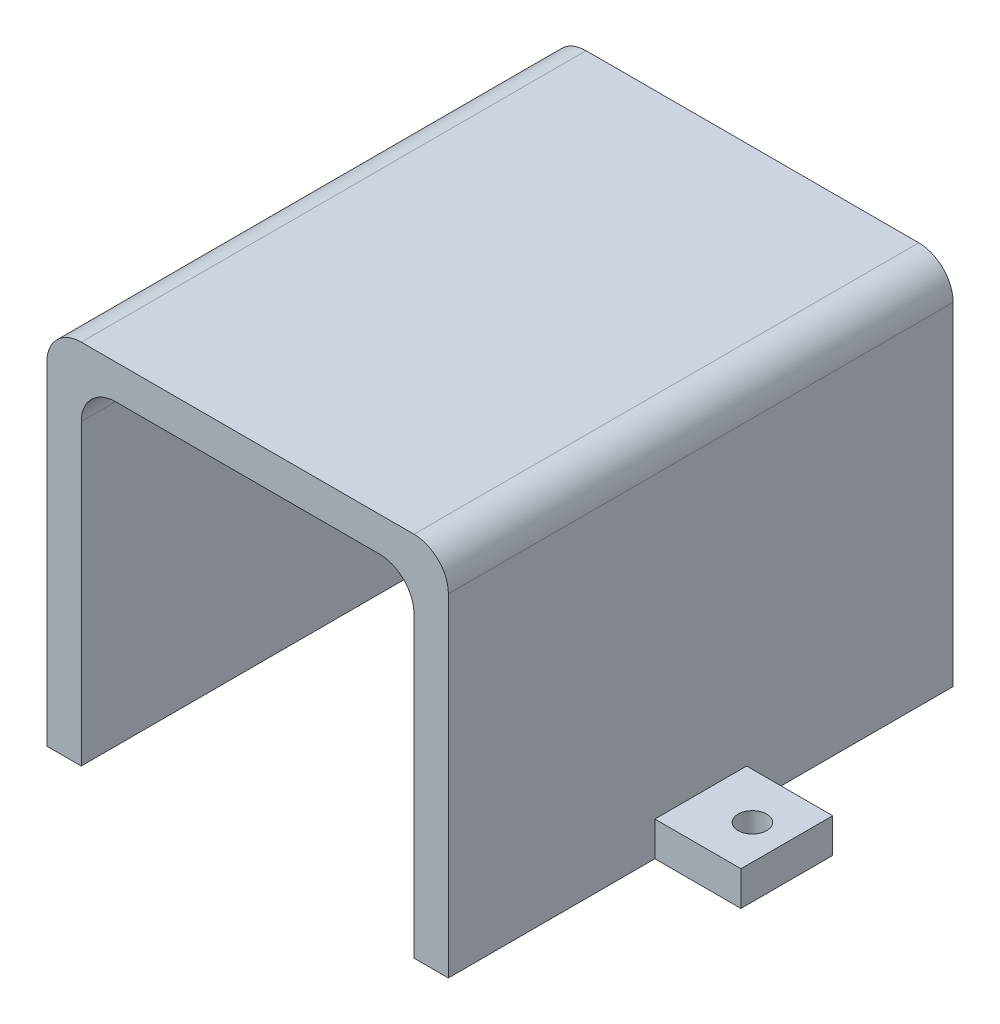
SolidWorks part; units mm, degrees
material "Malleable Cast Iron"
ref_plane "Front Plane" through (0, 0, 0) normal (0, 0, 1) x (1, 0, 0)
ref_plane "Top Plane" through (0, 0, 0) normal (0, 1, 0) x (1, 0, 0)
ref_plane "Right Plane" through (0, 0, 0) normal (1, 0, 0) x (0, 0, -1)
sketch "Sketch1" plane through (0, 0, 0) normal (0, 0, 1) x (1, 0, 0)
  line L0 (-17.5, -15) -> (-17.5, 17)
  line L1 (-17.5, 17) -> (17.5, 17)
  line L2 (-14.5, -15) -> (-14.5, 14)
  line L3 (-14.5, 14) -> (14.5, 14)
  line L4 (14.5, -15) -> (14.5, 14)
  line L5 (17.5, -15) -> (17.5, 17)
  line L6 (-17.5, -15) -> (-14.5, -15)
  line L7 (14.5, -15) -> (17.5, -15)
  point P0 (0, 0)
  point P10 (0, 14)
  dimension "D1" = 29
  dimension "D3" = 29
  dimension "D2" = 3
extrude "Boss-Extrude1" add sketch "Sketch1" along normal mid plane 44
sketch "Sketch2" plane through (0, -15, 0) normal (0, -1, 0) x (-1, 0, 0)
  line L0 (-17.5, -22) -> (-17.5, 22) construction
  line L1 (-17.5, 4) -> (-25, 4)
  line L2 (-17.5, 4) -> (-17.5, -4)
  line L3 (-17.5, -4) -> (-25, -4)
  line L4 (-25, 4) -> (-25, -4)
  line L5 (0, 25.0251) -> (0, -25.8998) construction
  line L6 (25, 4) -> (25, -4)
  line L7 (17.5, -4) -> (25, -4)
  line L8 (17.5, 4) -> (17.5, -4)
  line L9 (17.5, 4) -> (25, 4)
  circle A0 centre (-22, 0) radius 0.5
  circle A1 centre (22, 0) radius 0.5
  point P6 (-17.5, 0)
  dimension "D3" = 1
  dimension "D1" = 7.5
  dimension "D2" = 8
  dimension "D4" = 3
extrude "Boss-Extrude2" add sketch "Sketch2" against normal blind 3 separate body
fillet "Fillet1" radius 3 4 edges at (14.5, 14, 0) (-14.5, 14, 0) (-17.5, 17, 0) (17.5, 17, 0)
sketch "Sketch4" plane through (0, -15, 0) normal (0, -1, 0) x (-1, 0, 0)
  point P0 (-22, 0)
  point P1 (22, 0)
hole_wizard "M3x0.5 Tapped Hole1" positions "3DSketch2" profile "Sketch5" tap size "M3x0.5" standard "ANSI Metric"
sketch3d "3DSketch2"
  point P0 (-22, -15, 0)
  point P3 (22, -15, 0)
sketch "Sketch5" plane through (-22, -15, 0) normal (1, 0, 0) x (0, 0, -1)
  line L0 (0, 0) -> (0, 3.7511)
  line L1 (0, 3.7511) -> (1.25, 3)
  line L2 (1.25, 3) -> (1.25, 0)
  line L5 (1.25, 0) -> (0, 0)
  line L10 (0, 3.7511) -> (-1.25, 3) construction
  line L11 (0, -6.35) -> (0, 107.95) construction
  dimension "Tap Drill Dia." = 2.5
  dimension "Tap Drill Depth" = 3
  dimension "Drill Angle" = 118
